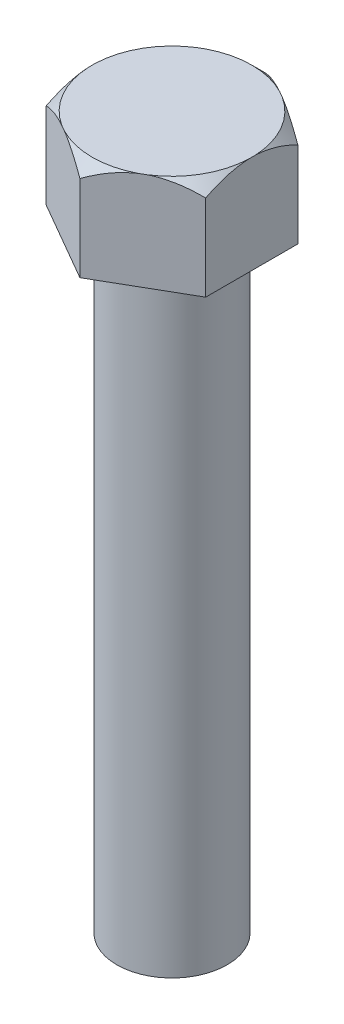
SolidWorks part; units mm, degrees
ref_plane "Front Plane" through (0, 0, 0) normal (0, 0, 1) x (1, 0, 0)
ref_plane "Top Plane" through (0, 0, 0) normal (0, 1, 0) x (1, 0, 0)
ref_plane "Right Plane" through (0, 0, 0) normal (1, 0, 0) x (0, 0, -1)
sketch "Sketch1" plane through (0, 0, 0) normal (0, 1, 0) x (1, 0, 0)
  circle A0 centre (0, 0) radius 2.25
  dimension "D1" = 4.5
extrude "Boss-Extrude1" add sketch "Sketch1" along normal blind 25
sketch "Sketch2" plane through (0, 25, 0) normal (0, 1, 0) x (1, 0, 0)
  line L0 (0, 0) -> (0, -1.4883) construction
  line L1 (-3.25, -1.8764) -> (0, -3.7528)
  line L2 (0, -3.7528) -> (3.25, -1.8764)
  line L3 (3.25, -1.8764) -> (3.25, 1.8764)
  line L4 (3.25, 1.8764) -> (0, 3.7528)
  line L5 (0, 3.7528) -> (-3.25, 1.8764)
  line L6 (-3.25, 1.8764) -> (-3.25, -1.8764)
  circle A0 centre (0, 0) radius 3.25 construction
  dimension "D1" = 6.5
extrude "Boss-Extrude2" add sketch "Sketch2" along normal blind 4
sketch "Sketch4" plane through (0, 0, 0) normal (1, 0, 0) x (0, 0, -1)
  line L0 (3.2528, 29) -> (3.7528, 28.5)
  line L1 (1.8764, 29) -> (3.7528, 29) construction
  line L2 (3.7528, 29) -> (3.7528, 25) construction
  line L3 (3.7528, 28.5) -> (3.7528, 29)
  line L4 (3.7528, 29) -> (3.2528, 29)
  line L5 (0, 0) -> (0, 15.6013) construction
  dimension "D1" = 0.5
  dimension "D2" = 0.5
revolve "Cut-Revolve1" cut sketch "Sketch4" angle 360 about L5
